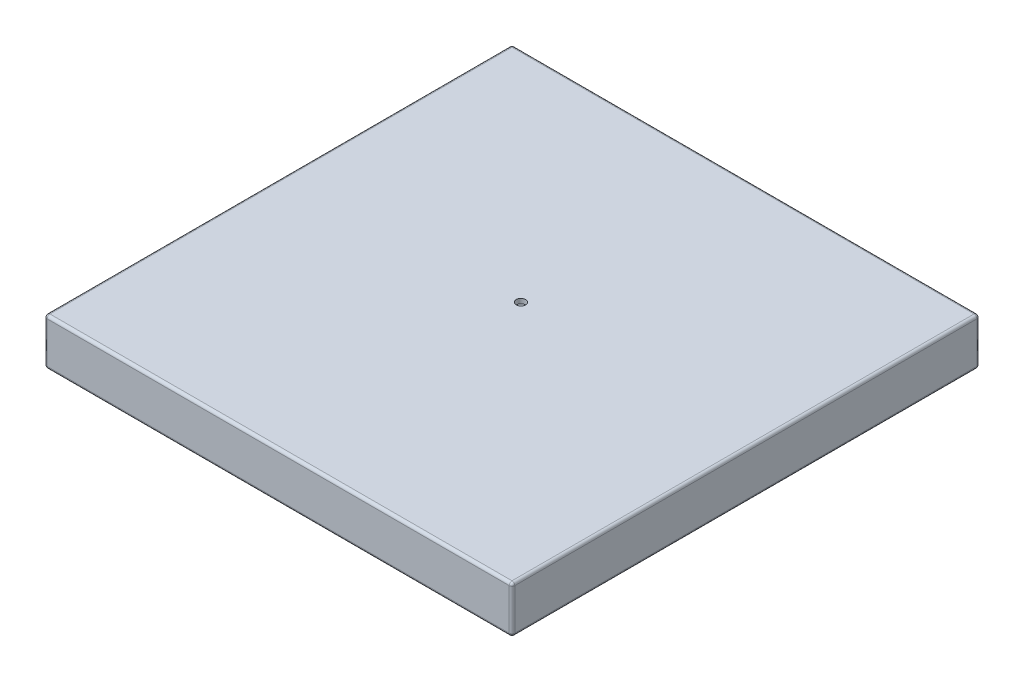
SolidWorks part; units mm, degrees
ref_plane "Front Plane" through (0, 0, 0) normal (0, 0, 1) x (1, 0, 0)
ref_plane "Top Plane" through (0, 0, 0) normal (0, 1, 0) x (1, 0, 0)
ref_plane "Right Plane" through (0, 0, 0) normal (1, 0, 0) x (0, 0, -1)
sketch "Sketch1" plane through (0, 0, 0) normal (0, 1, 0) x (1, 0, 0)
  line L1 (0, 0) -> (50, 0)
  line L2 (0, 0) -> (0, -50)
  line L3 (0, -50) -> (50, -50)
  line L4 (50, 0) -> (50, -50)
  dimension "D1" = 50
  dimension "D2" = 50
extrude "Boss-Extrude1" add sketch "Sketch1" along normal blind 5
sketch "Sketch2" plane through (0, 0, 0) normal (0, 0, -1) x (-1, 0, 0)
  line L0 (-0.5, 0.5) -> (0, 0.5) construction
  line L1 (-49.5, 4.5) -> (-0.5, 4.5)
  line L2 (-49.5, 4.5) -> (-49.5, 0.5)
  line L3 (-49.5, 0.5) -> (-0.5, 0.5)
  line L4 (-0.5, 4.5) -> (-0.5, 0.5)
  line L5 (0, 5) -> (0, 0) construction
  line L6 (-0.5, 0.5) -> (-0.5, 0) construction
  line L7 (-50, 0) -> (0, 0) construction
  line L8 (-49.5, 4.5) -> (-49.5, 5) construction
  line L9 (-50, 5) -> (0, 5) construction
  line L10 (-49.5, 4.5) -> (-50, 4.5) construction
  line L11 (-50, 5) -> (-50, 0) construction
  dimension "D1" = 0.5
  dimension "D2" = 0.5
  dimension "D3" = 0.5
  dimension "D4" = 0.5
extrude "Cut-Extrude1" cut sketch "Sketch2" against normal blind 49.5
sketch "Sketch3" plane through (0, 5, 0) normal (0, 1, 0) x (1, 0, 0)
  circle A0 centre (24.3845, -23.4331) radius 0.5
  dimension "D1" = 1
extrude "Cut-Extrude2" cut sketch "Sketch3" against normal through all
fillet "Fillet6" radius 0.3 20 edges at (0.5, 0.5, 24.75) (25, 0.5, 49.5) (49.5, 0.5, 24.75) (0.5, 2.5, 49.5) (0.5, 4.5, 24.75) (49.5, 4.5, 24.75) (49.5, 2.5, 49.5) (25, 4.5, 49.5) (25, 5, 0) (0, 2.5, 0) (25, 0, 0) (50, 2.5, 0) (50, 0, 25) (50, 5, 25) (50, 2.5, 50) (25, 0, 50) (25, 5, 50) (0, 2.5, 50) (0, 5, 25) (0, 0, 25)
